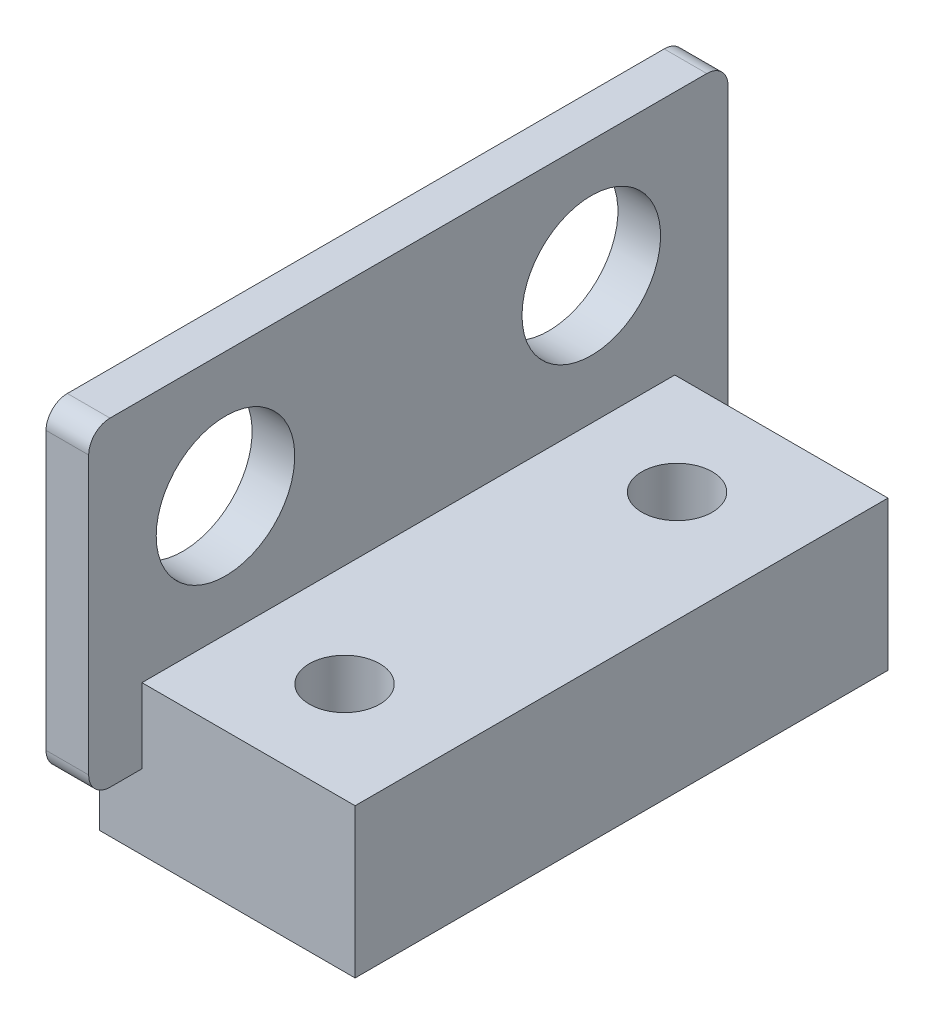
SolidWorks part; units mm, degrees
ref_plane "Front Plane" through (0, 0, 0) normal (0, 0, 1) x (1, 0, 0)
ref_plane "Top Plane" through (0, 0, 0) normal (0, 1, 0) x (1, 0, 0)
ref_plane "Right Plane" through (0, 0, 0) normal (1, 0, 0) x (0, 0, -1)
sketch "Sketch1" plane through (0, 0, 0) normal (0, 1, 0) x (1, 0, 0)
  line L0 (-4.8636, 0) -> (9.0813, 0) construction
  line L1 (-6, 12.5) -> (6, 12.5)
  line L2 (-6, 12.5) -> (-6, -12.5)
  line L3 (-6, -12.5) -> (6, -12.5)
  line L4 (6, 12.5) -> (6, -12.5)
  line L5 (-6, 12.5) -> (6, -12.5) construction
  line L6 (-6, -12.5) -> (6, 12.5) construction
  line L11 (4.5, -7.8) -> (2.6525, -4.6) construction
  line L12 (2.6525, -4.6) -> (-1.0426, -4.6) construction
  line L13 (-1.0426, -4.6) -> (-2.8901, -7.8) construction
  line L14 (-2.8901, -7.8) -> (-1.0426, -11) construction
  line L15 (-1.0426, -11) -> (2.6525, -11) construction
  line L16 (2.6525, -11) -> (4.5, -7.8) construction
  line L17 (2.6525, 11) -> (4.5, 7.8) construction
  line L18 (-1.0426, 11) -> (2.6525, 11) construction
  line L19 (-2.8901, 7.8) -> (-1.0426, 11) construction
  line L20 (-1.0426, 4.6) -> (-2.8901, 7.8) construction
  line L21 (2.6525, 4.6) -> (-1.0426, 4.6) construction
  line L22 (4.5, 7.8) -> (2.6525, 4.6) construction
  circle A0 centre (0.805, -7.8) radius 1.65
  circle A1 centre (0.805, -7.8) radius 3.2 construction
  circle A2 centre (0.805, 7.8) radius 3.2 construction
  circle A3 centre (0.805, 7.8) radius 1.65
  point P0 (0, 0)
  dimension "D3" = 3.3
  dimension "D1" = 12
  dimension "D2" = 25
  dimension "D4" = 6.4
  dimension "D5" = 1.5
  dimension "D6" = 1.5
extrude "Boss-Extrude1" add sketch "Sketch1" along normal mid plane 7
sketch "Sketch2" plane through (0, -3.5, 0) normal (0, -1, 0) x (1, 0, 0)
  line L1 (2.6525, 4.6) -> (4.5, 7.8)
  line L2 (4.5, 7.8) -> (2.6525, 11)
  line L3 (2.6525, 11) -> (-1.0426, 11)
  line L4 (-1.0426, 11) -> (-2.8901, 7.8)
  line L5 (-2.8901, 7.8) -> (-1.0426, 4.6)
  line L6 (-1.0426, 4.6) -> (2.6525, 4.6)
  line L7 (2.6525, -11) -> (4.5, -7.8)
  line L8 (4.5, -7.8) -> (2.6525, -4.6)
  line L9 (2.6525, -4.6) -> (-1.0426, -4.6)
  line L10 (-1.0426, -4.6) -> (-2.8901, -7.8)
  line L11 (-2.8901, -7.8) -> (-1.0426, -11)
  line L12 (-1.0426, -11) -> (2.6525, -11)
  circle A0 centre (0.805, 7.8) radius 3.2 construction
  circle A1 centre (0.805, -7.8) radius 3.2 construction
extrude "Cut-Extrude1" cut sketch "Sketch2" against normal blind 3.5
sketch "Sketch3" plane through (-6, 0, 0) normal (-1, 0, 0) x (0, 0, 1)
  line L0 (0, 0) -> (14, 0)
  line L1 (0, 0) -> (-14, 0)
  line L2 (-15, 1) -> (-15, 14)
  line L3 (-14, 15) -> (14, 15)
  line L4 (15, 14) -> (15, 1)
  line L6 (-3.9624, 9.5) -> (-6.2718, 13.5) construction
  line L7 (-6.2718, 13.5) -> (-10.8906, 13.5) construction
  line L8 (-10.8906, 13.5) -> (-13.2, 9.5) construction
  line L9 (-13.2, 9.5) -> (-10.8906, 5.5) construction
  line L10 (-10.8906, 5.5) -> (-6.2718, 5.5) construction
  line L11 (-6.2718, 5.5) -> (-3.9624, 9.5) construction
  line L12 (13.2, 9.1249) -> (10.8906, 13.1249) construction
  line L13 (10.8906, 13.1249) -> (6.2718, 13.1249) construction
  line L14 (6.2718, 13.1249) -> (3.9624, 9.1249) construction
  line L15 (3.9624, 9.1249) -> (6.2718, 5.1249) construction
  line L16 (6.2718, 5.1249) -> (10.8906, 5.1249) construction
  line L17 (10.8906, 5.1249) -> (13.2, 9.1249) construction
  arc A0 (-14, 0) -> (-15, 1) centre (-14, 1) cw
  arc A1 (14, 0) -> (15, 1) centre (14, 1) ccw
  arc A2 (14, 15) -> (15, 14) centre (14, 14) cw
  arc A3 (-15, 14) -> (-14, 15) centre (-14, 14) cw
  circle A4 centre (-8.5812, 9.5) radius 3.25
  circle A5 centre (8.5812, 9.1249) radius 3.25
  circle A6 centre (-8.5812, 9.5) radius 4 construction
  circle A7 centre (8.5812, 9.1249) radius 4 construction
  point P8 (-15, 0)
  point P11 (15, 0)
  point P16 (-15, 15)
  dimension "D4" = 1
  dimension "D5" = 6.5
  dimension "D6" = 6.5
  dimension "D1" = 15
  dimension "D2" = 15
  dimension "D3" = 15
  dimension "D7" = 8
  dimension "D8" = 1.5
  dimension "D9" = 1.8
  dimension "D10" = 8
  dimension "D11" = 1.8
extrude "Boss-Extrude2" add sketch "Sketch3" against normal blind 2
